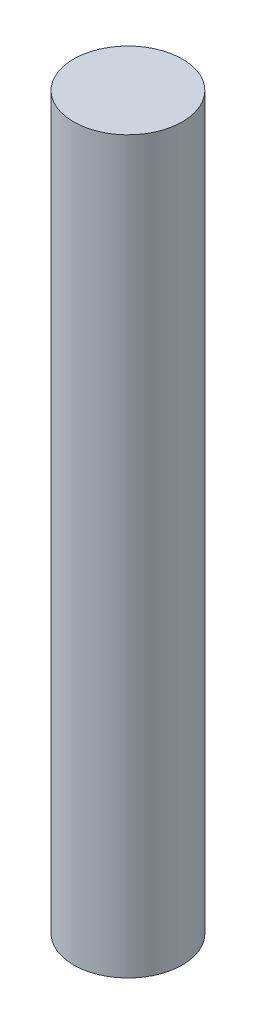
SolidWorks part; units mm, degrees
ref_plane "前视基准面" through (0, 0, 0) normal (0, 0, 1) x (1, 0, 0)
ref_plane "上视基准面" through (0, 0, 0) normal (0, 1, 0) x (1, 0, 0)
ref_plane "右视基准面" through (0, 0, 0) normal (1, 0, 0) x (0, 0, -1)
sketch "草图1" plane through (0, 0, 0) normal (0, 1, 0) x (1, 0, 0)
  circle A0 centre (0, 0) radius 7.45
  dimension "D1" = 14.9
extrude "凸台-拉伸1" add sketch "草图1" along normal blind 100
